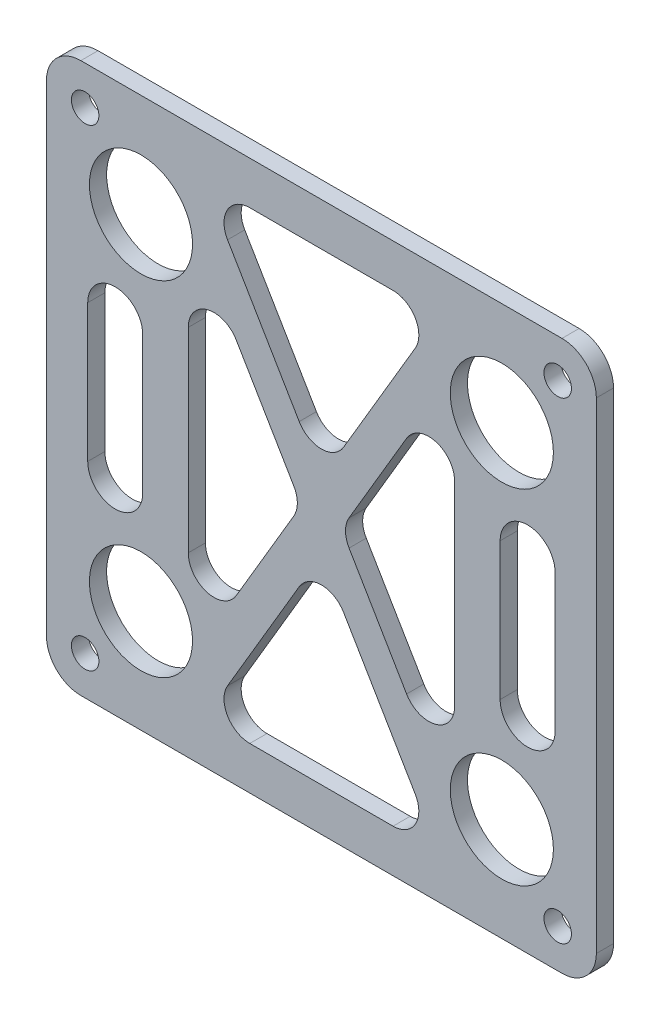
SolidWorks part; units mm, degrees
ref_plane "前视基准面" through (0, 0, 0) normal (0, 0, 1) x (1, 0, 0)
ref_plane "上视基准面" through (0, 0, 0) normal (0, 1, 0) x (1, 0, 0)
ref_plane "右视基准面" through (0, 0, 0) normal (1, 0, 0) x (0, 0, -1)
sketch "草图1" plane through (0, 0, 0) normal (0, 0, 1) x (1, 0, 0)
  line L1 (-32, 32) -> (32, 32)
  line L2 (-32, 32) -> (-32, -32)
  line L3 (-32, -32) -> (32, -32)
  line L4 (32, 32) -> (32, -32)
  line L5 (-32, 32) -> (32, -32) construction
  line L6 (-32, -32) -> (32, 32) construction
  point P0 (0, 0)
  dimension "D1" = 64
  dimension "D2" = 64
extrude "凸台-拉伸1" add sketch "草图1" along normal blind 2
sketch "草图2" plane through (0, 0, 2) normal (0, 0, 1) x (1, 0, 0)
  line L0 (0, 0) -> (0, 32) construction
  line L1 (-27.5, 27.5) -> (27.5, 27.5) construction
  line L2 (-27.5, 27.5) -> (-27.5, -27.5) construction
  line L3 (-27.5, -27.5) -> (27.5, -27.5) construction
  line L4 (27.5, 27.5) -> (27.5, -27.5) construction
  line L5 (-27.5, 27.5) -> (27.5, -27.5) construction
  line L6 (-27.5, -27.5) -> (27.5, 27.5) construction
  line L7 (32, 32) -> (-32, 32) construction
  circle A0 centre (-27.5, -27.5) radius 1.6
  circle A1 centre (-27.5, 27.5) radius 1.6
  circle A2 centre (27.5, -27.5) radius 1.6
  circle A3 centre (27.5, 27.5) radius 1.6
  point P0 (0, 0)
  dimension "D3" = 3.2
  dimension "D4" = 3.2
  dimension "D1" = 55
  dimension "D2" = 55
extrude "切除-拉伸1" cut sketch "草图2" against normal blind 2
fillet "圆角1" radius 4 4 edges at (32, -32, 1) (-32, -32, 1) (-32, 32, 1) (32, 32, 1)
sketch "草图3" plane through (0, 0, 2) normal (0, 0, 1) x (1, 0, 0)
  line L0 (0, 32) -> (0, -32) construction
  line L1 (28, 32) -> (-28, 32) construction
  line L2 (-28, -32) -> (28, -32) construction
  line L3 (-32, 28) -> (-32, -28) construction
  line L4 (-24, 8) -> (-24, -8) construction
  line L5 (-20.8, 8) -> (-20.8, -8)
  line L6 (-27.2, 8) -> (-27.2, -8)
  line L7 (-24, 0) -> (0, 0) construction
  line L9 (24, 8) -> (24, -8) construction
  line L10 (20.8, 8) -> (20.8, -8)
  line L11 (27.2, 8) -> (27.2, -8)
  arc A0 (-20.8, 8) -> (-27.2, 8) centre (-24, 8) ccw
  arc A1 (-27.2, -8) -> (-20.8, -8) centre (-24, -8) ccw
  arc A2 (20.8, 8) -> (27.2, 8) centre (24, 8) cw
  arc A3 (27.2, -8) -> (20.8, -8) centre (24, -8) cw
  point P12 (-24, 0)
  point P22 (24, 0)
  dimension "D2" = 3.2
  dimension "D4" = 90
  dimension "D1" = 8
  dimension "D3" = 8
extrude "切除-拉伸2" cut sketch "草图3" against normal blind 10
sketch "草图4" plane through (0, 0, 2) normal (0, 0, 1) x (1, 0, 0)
  line L0 (-15.4983, 22.3632) -> (-15.4983, -22.3632)
  line L1 (-16.4983, 28) -> (16.4983, 28) construction
  line L2 (-16.4983, 28) -> (-16.4983, -28) construction
  line L3 (-16.4983, -28) -> (16.4983, -28) construction
  line L4 (16.4983, 28) -> (16.4983, -28) construction
  line L5 (-16.4983, 28) -> (16.4983, -28) construction
  line L6 (-16.4983, -28) -> (16.4983, 28) construction
  line L7 (-15.4983, -22.3632) -> (-2.3214, 0)
  line L8 (-2.3214, 0) -> (-15.4983, 22.3632)
  line L9 (-13.5877, -27) -> (13.5877, -27)
  line L10 (13.5877, -27) -> (0, -3.9397)
  line L11 (0, -3.9397) -> (-13.5877, -27)
  line L12 (0, 0) -> (16.4983, 0) construction
  line L13 (0, 0) -> (0, 28) construction
  line L14 (2.3214, 0) -> (15.4983, 22.3632)
  line L15 (15.4983, -22.3632) -> (2.3214, 0)
  line L16 (15.4983, 22.3632) -> (15.4983, -22.3632)
  line L17 (0, 3.9397) -> (-13.5877, 27)
  line L18 (13.5877, 27) -> (0, 3.9397)
  line L19 (-13.5877, 27) -> (13.5877, 27)
  point P0 (0, 0)
  dimension "D1" = 56
  dimension "D2" = 32.9966
  dimension "D3" = 2
  dimension "D4" = 1
  dimension "D5" = 2
  dimension "D6" = 2
  dimension "D7" = 1
  dimension "D8" = 2
extrude "切除-拉伸3" cut sketch "草图4" against normal blind 10
fillet "圆角2" radius 3 12 edges at (-15.4983, 22.3632, 1) (-2.3214, 0, 1) (-15.4983, -22.3632, 1) (-13.5877, 27, 1) (13.5877, 27, 1) (0, 3.9397, 1) (13.5877, -27, 1) (-13.5877, -27, 1) (0, -3.9397, 1) (15.4983, 22.3632, 1) (15.4983, -22.3632, 1) (2.3214, 0, 1)
sketch "草图5" plane through (0, 0, 2) normal (0, 0, 1) x (1, 0, 0)
  line L0 (0, 0) -> (32, 0) construction
  line L1 (32, -28) -> (32, 28) construction
  line L2 (0, 0) -> (0, 32) construction
  line L3 (28, 32) -> (-28, 32) construction
  circle A0 centre (21, 20) radius 6
  circle A1 centre (-21, 20) radius 6
  circle A2 centre (21, -20) radius 6
  circle A3 centre (-21, -20) radius 6
  dimension "D1" = 20
  dimension "D2" = 21
  dimension "D3" = 12
extrude "切除-拉伸4" cut sketch "草图5" against normal blind 10
